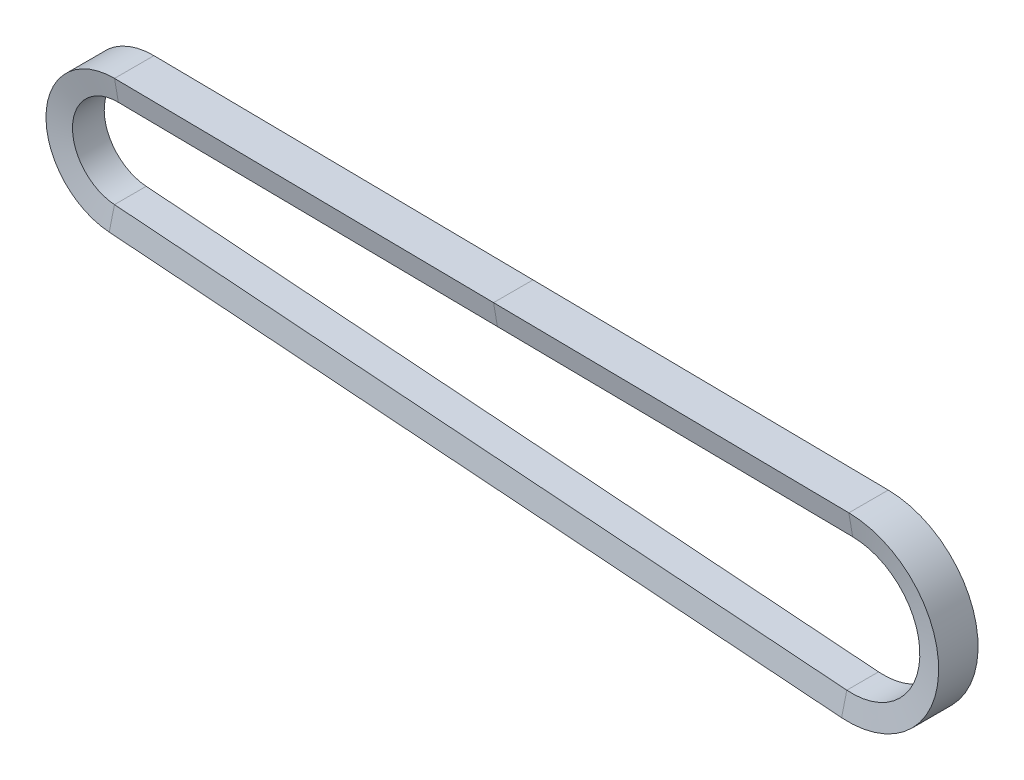
SolidWorks part; units mm, degrees
ref_plane "Front Plane" through (0, 0, 0) normal (0, 0, 1) x (1, 0, 0)
ref_plane "Top Plane" through (0, 0, 0) normal (0, 1, 0) x (1, 0, 0)
ref_plane "Right Plane" through (0, 0, 0) normal (1, 0, 0) x (0, 0, -1)
sketch "Sketch1" plane through (0, 0, 0) normal (0, 0, 1) x (1, 0, 0)
  line L0 (-83.7447, 6.1388) -> (-82.7447, 6.1388) construction
  line L1 (-83.7447, 6.1388) -> (-83.7447, 7.1388) construction
  line L2 (-83.6212, 16.1381) -> (78.3746, 14.1377)
  line L3 (77.0796, -15.8201) -> (-84.4846, -3.8338)
  arc A0 (-84.4846, -3.8338) -> (-83.6212, 16.1381) centre (-83.7447, 6.1388) cw
  arc A1 (78.3746, 14.1377) -> (77.0796, -15.8201) centre (78.1894, -0.8612) cw
sketch "Sketch2" plane through (0, 0, 0) normal (1, 0, 0) x (0, 0, -1)
  line L0 (-3.5, 15.1055) -> (3.5, 15.1055)
  line L3 (-4.3477, 20.1055) -> (4.3477, 20.1055)
  line L4 (-4.3477, 20.1055) -> (-3.5, 15.1055)
  line L5 (3.5, 15.1055) -> (4.3477, 20.1055)
  point P4 (0, 20.1055)
  point P5 (0, 15.1055)
  dimension "D1" = 7
  dimension "D2" = 5
sweep "Sweep1" add profiles "Sketch2" path "Sketch1"
